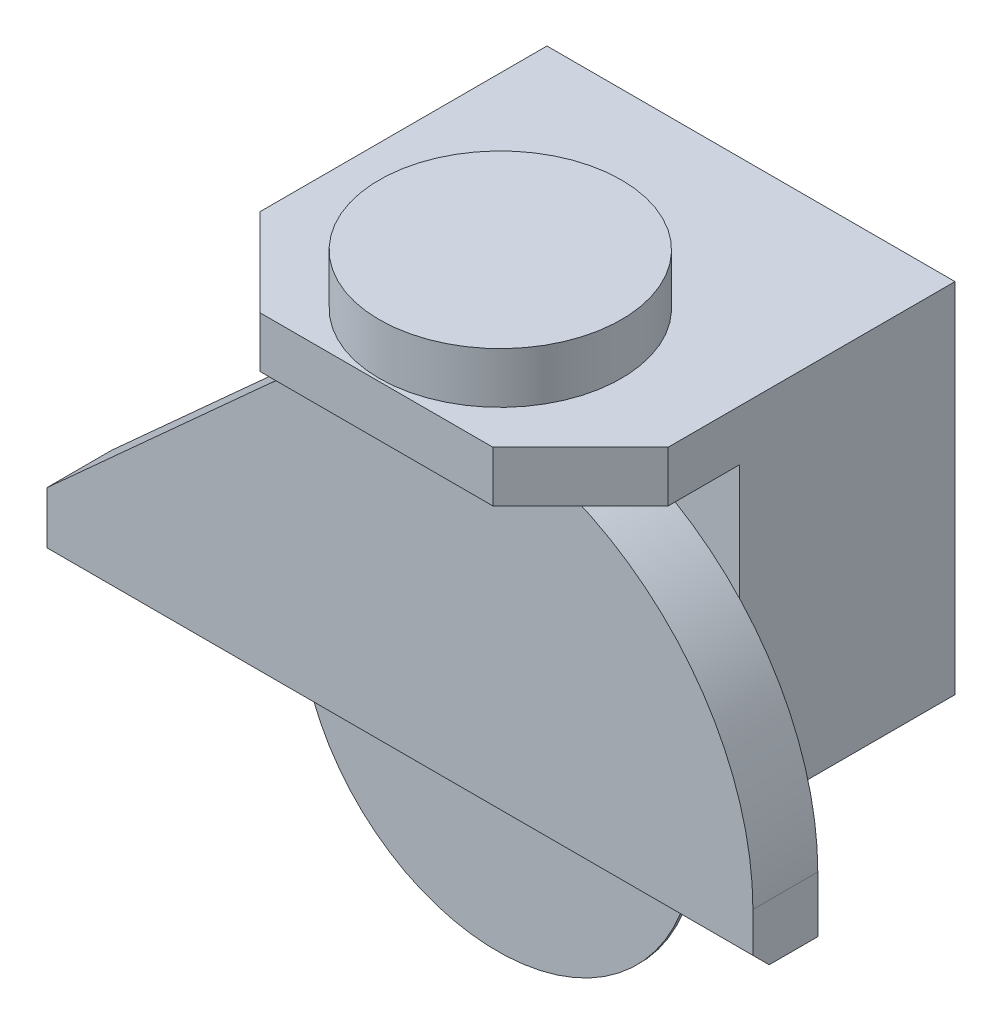
SolidWorks part; units mm, degrees
ref_plane "Front Plane" through (0, 0, 0) normal (0, 0, 1) x (1, 0, 0)
ref_plane "Top Plane" through (0, 0, 0) normal (0, 1, 0) x (1, 0, 0)
ref_plane "Right Plane" through (0, 0, 0) normal (1, 0, 0) x (0, 0, -1)
sketch "Sketch1" plane through (0, 0, 0) normal (0, 0, 1) x (1, 0, 0)
  circle A0 centre (0, 0) radius 225
  dimension "D1" = 450
extrude "Boss-Extrude1" add sketch "Sketch1" along normal blind 3.5
sketch "Sketch2" plane through (0, 0, 0) normal (0, 0, -1) x (-1, 0, 0)
  circle A0 centre (0, 0) radius 105.8638
extrude "Boss-Extrude2" add sketch "Sketch2" along normal blind 350
sketch "Sketch3" plane through (0, 0, 0) normal (0, 1, 0) x (1, 0, 0)
  line L0 (0, 0) -> (0, 39.8369) construction
  line L1 (-232.6858, 285.8733) -> (232.6858, 285.8733)
  line L2 (-232.6858, 285.8733) -> (-232.6858, 39.8369)
  line L3 (-232.6858, 39.8369) -> (232.6858, 39.8369)
  line L4 (232.6858, 285.8733) -> (232.6858, 39.8369)
  line L5 (225, 0) -> (-225, 0) construction
extrude "Boss-Extrude3" add sketch "Sketch3" along normal blind 350
sketch "Sketch4" plane through (0, 0, 3.5) normal (0, 0, 1) x (1, 0, 0)
  line L0 (-475.5246, -63.9311) -> (329.5666, -63.9311)
  line L1 (-475.5246, -63.9311) -> (-475.5246, 14.1297)
  line L2 (-475.5246, 14.1297) -> (-221.1485, 244.3512)
  line L3 (329.5666, 0) -> (329.5666, -63.9311)
  arc A0 (329.5666, 0) -> (-221.1485, 244.3512) centre (0, 0) ccw
  point P1 (-475.5246, 14.1297)
extrude "Boss-Extrude4" add sketch "Sketch4" along normal blind 38 and the other way blind 36
sketch "Sketch5" plane through (329.5666, 0, 0) normal (1, 0, 0) x (0, 0, -1)
  line L0 (-41.5, -63.9311) -> (-41.5, -45.3968)
  line L1 (-41.5, -63.9311) -> (-41.5, 0) construction
  line L2 (-41.5, -45.3968) -> (-22.9656, -63.9311)
  line L3 (32.5, -63.9311) -> (-41.5, -63.9311) construction
  line L4 (-22.9656, -63.9311) -> (-41.5, -63.9311)
  point P5 (-20.1858, -63.9311)
  point P9 (-22.9656, -63.9311)
extrude "Cut-Extrude1" cut sketch "Sketch5" against normal blind 1011
sketch "Sketch6" plane through (0, 350, 0) normal (0, 1, 0) x (1, 0, 0)
  line L0 (232.6858, 39.8369) -> (232.6858, 285.8733) construction
  line L1 (-232.6858, 285.8733) -> (232.6858, 285.8733)
  line L2 (-232.6858, 285.8733) -> (-232.6858, -41.2304)
  line L3 (-132.6858, -141.2304) -> (132.6858, -141.2304)
  line L4 (232.6858, 285.8733) -> (232.6858, -41.2304)
  line L5 (-232.6858, -41.2304) -> (-132.6858, -141.2304)
  line L6 (132.6858, -141.2304) -> (232.6858, -41.2304)
  point P1 (232.6858, -141.2304)
  point P2 (-232.6858, -141.2304)
extrude "Boss-Extrude5" add sketch "Sketch6" along normal blind 58
sketch "Sketch7" plane through (0, 408, 0) normal (0, 1, 0) x (1, 0, 0)
  circle A0 centre (0, 0) radius 138.0831
extrude "Boss-Extrude6" add sketch "Sketch7" along normal blind 58
